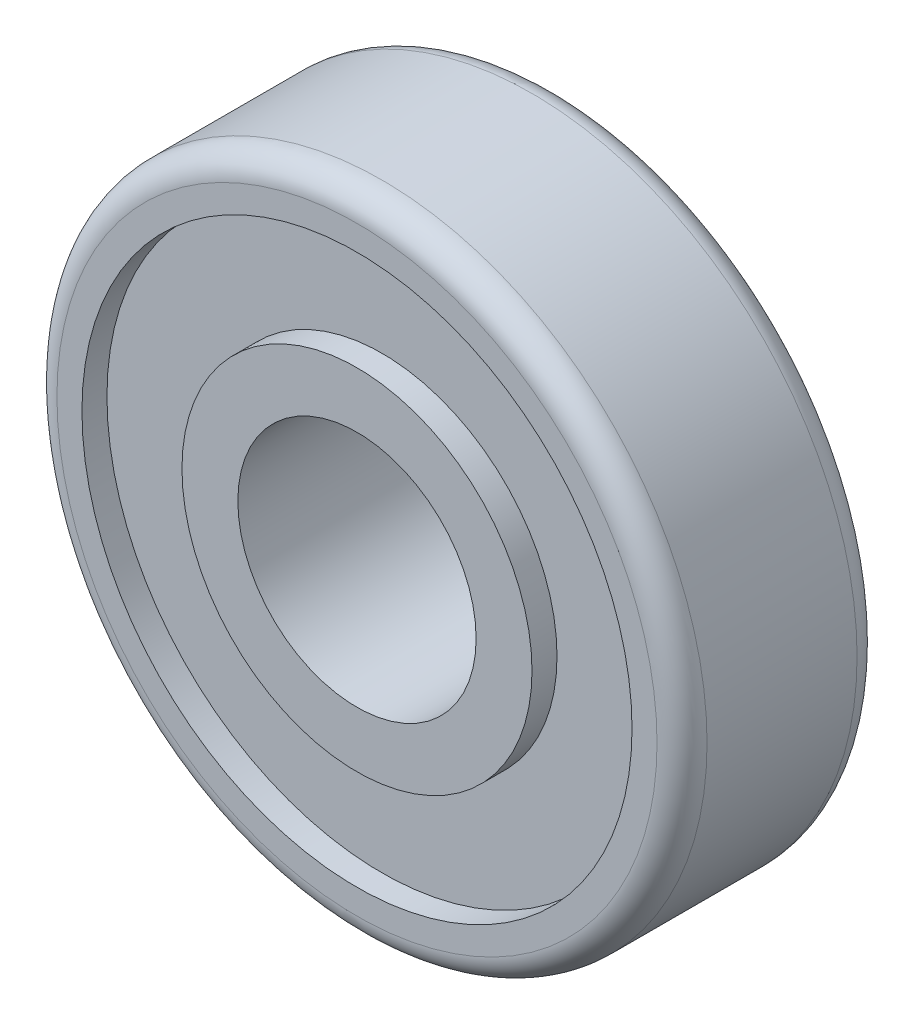
SolidWorks part; units mm, degrees
ref_plane "Plano frontal" through (0, 0, 0) normal (0, 0, 1) x (1, 0, 0)
ref_plane "Plano superior" through (0, 0, 0) normal (0, 1, 0) x (1, 0, 0)
ref_plane "Plano direito" through (0, 0, 0) normal (1, 0, 0) x (0, 0, -1)
sketch "Esboço1" plane through (0, 0, 0) normal (0, 0, 1) x (1, 0, 0)
  circle A0 centre (0, 0) radius 13
  circle A1 centre (0, 0) radius 4.765
  dimension "D1" = 26
  dimension "D2" = 9.53
extrude "Ressalto-extrusão1" add sketch "Esboço1" along normal blind 8
sketch "Esboço2" plane through (0, 0, 8) normal (0, 0, 1) x (1, 0, 0)
  circle A0 centre (0, 0) radius 11
  circle A1 centre (0, 0) radius 7
  dimension "D1" = 22
  dimension "D2" = 14
extrude "Corte-extrusão1" cut sketch "Esboço2" against normal blind 1
sketch "Esboço3" plane through (0, 0, 0) normal (0, 0, -1) x (-1, 0, 0)
  circle A0 centre (0, 0) radius 11
  circle A1 centre (0, 0) radius 7
  dimension "D1" = 22
  dimension "D2" = 14
extrude "Corte-extrusão2" cut sketch "Esboço3" against normal blind 1
fillet "Filete1" radius 1 2 edges at (13, 0, 0) (13, 0, 8)
